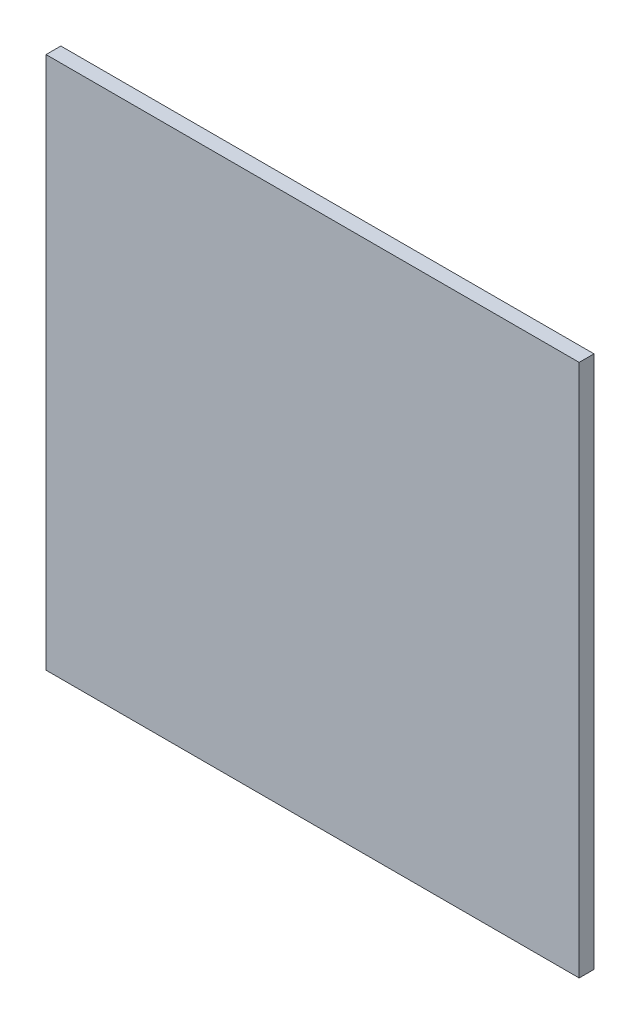
SolidWorks part; units mm, degrees
ref_plane "Front Plane" through (0, 0, 0) normal (0, 0, 1) x (1, 0, 0)
ref_plane "Top Plane" through (0, 0, 0) normal (0, 1, 0) x (1, 0, 0)
ref_plane "Right Plane" through (0, 0, 0) normal (1, 0, 0) x (0, 0, -1)
sketch "Sketch1" plane through (0, 0, 0) normal (0, 0, 1) x (1, 0, 0)
  line L1 (-45, -45) -> (45, -45)
  line L2 (-45, -45) -> (-45, 45)
  line L3 (-45, 45) -> (45, 45)
  line L4 (45, -45) -> (45, 45)
  line L5 (-45, -45) -> (45, 45) construction
  line L6 (-45, 45) -> (45, -45) construction
  line L7 (-42.5, -28) -> (42.5, -28) construction
  line L8 (-42.5, -28) -> (-42.5, 28) construction
  line L9 (-42.5, 28) -> (42.5, 28) construction
  line L10 (42.5, -28) -> (42.5, 28) construction
  line L11 (-42.5, -28) -> (42.5, 28) construction
  line L12 (-42.5, 28) -> (42.5, -28) construction
  line L13 (-19, -24.5) -> (39, -24.5) construction
  line L14 (-19, -24.5) -> (-19, 24.5) construction
  line L15 (-19, 24.5) -> (39, 24.5) construction
  line L16 (39, -24.5) -> (39, 24.5) construction
  line L17 (-19, -24.5) -> (39, 24.5) construction
  line L18 (-19, 24.5) -> (39, -24.5) construction
  point P0 (0, 0)
  point P6 (0, 0)
  point P11 (10, 0)
  dimension "D1" = 90
  dimension "D2" = 56
  dimension "D3" = 85
  dimension "D4" = 3.5
  dimension "D5" = 49
  dimension "D6" = 58
extrude "Boss-Extrude1" add sketch "Sketch1" along normal mid plane 2.5
